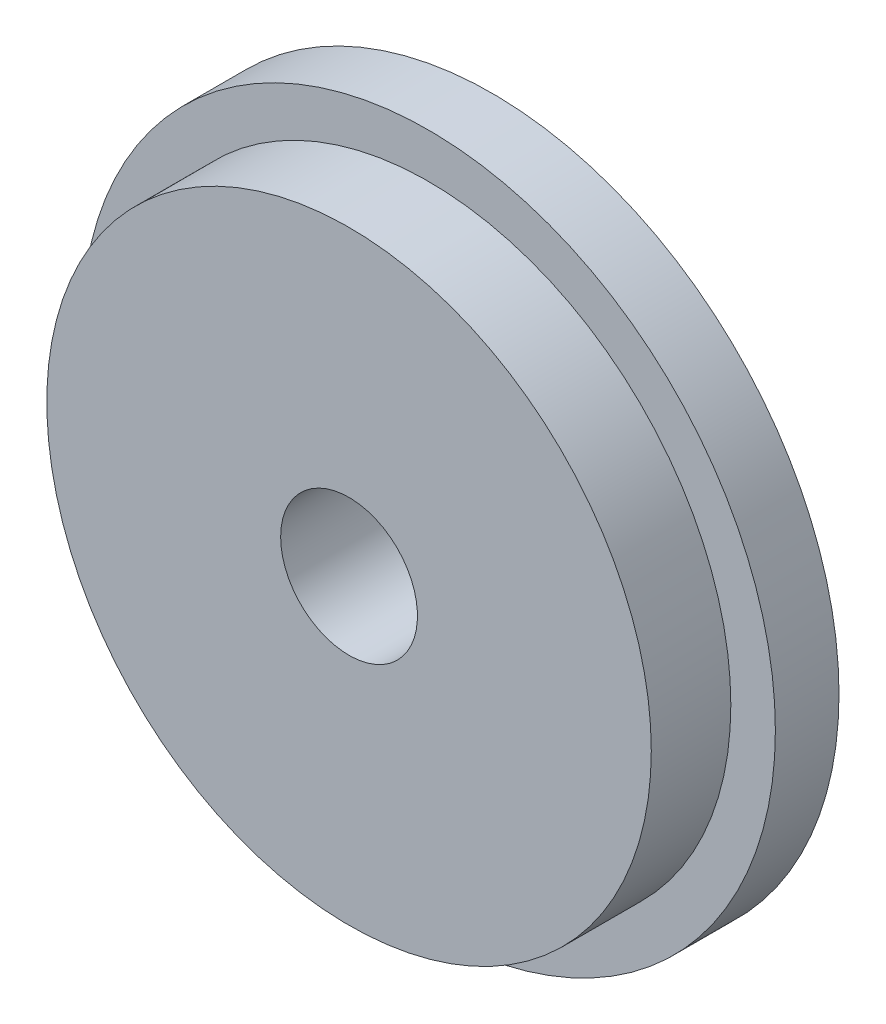
SolidWorks part; units mm, degrees
ref_plane "Front Plane" through (0, 0, 0) normal (0, 0, 1) x (1, 0, 0)
ref_plane "Top Plane" through (0, 0, 0) normal (0, 1, 0) x (1, 0, 0)
ref_plane "Right Plane" through (0, 0, 0) normal (1, 0, 0) x (0, 0, -1)
sketch "Sketch1" plane through (0, 0, 0) normal (0, 0, 1) x (1, 0, 0)
  circle A0 centre (0, 0) radius 10.9
  dimension "D1" = 21.8
extrude "Boss-Extrude1" add sketch "Sketch1" along normal blind 2
sketch "Sketch2" plane through (0, 0, 2) normal (0, 0, 1) x (1, 0, 0)
  circle A0 centre (0, 0) radius 9.5
  dimension "D1" = 19
extrude "Boss-Extrude2" add sketch "Sketch2" along normal blind 2.5
sketch "Sketch3" plane through (0, 0, 0) normal (0, 0, -1) x (-1, 0, 0)
  circle A0 centre (0, 0) radius 2.15
  dimension "D1" = 4.3
extrude "Cut-Extrude1" cut sketch "Sketch3" against normal through all
